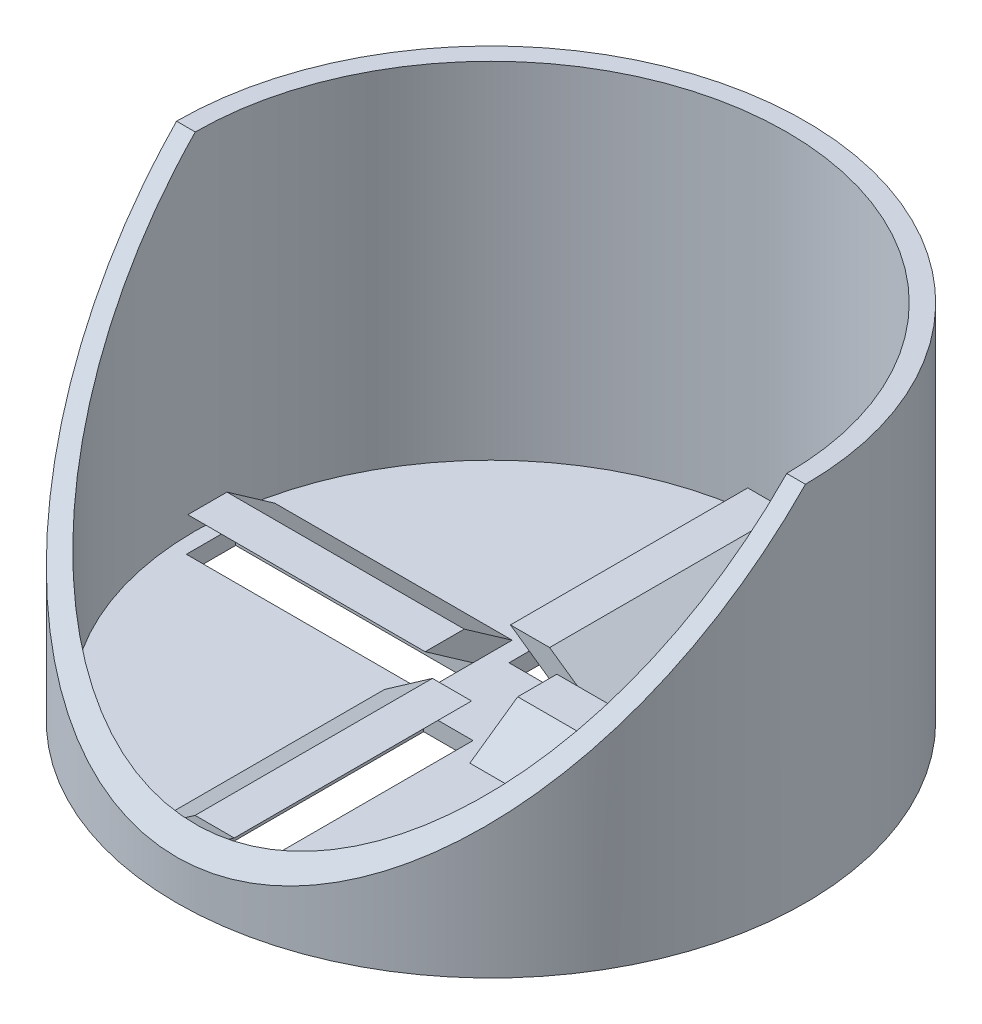
SolidWorks part; units mm, degrees
ref_plane "Front Plane" through (0, 0, 0) normal (0, 0, 1) x (1, 0, 0)
ref_plane "Top Plane" through (0, 0, 0) normal (0, 1, 0) x (1, 0, 0)
ref_plane "Right Plane" through (0, 0, 0) normal (1, 0, 0) x (0, 0, -1)
sketch "Sketch1" plane through (0, 0, 0) normal (0, 1, 0) x (1, 0, 0)
  circle A0 centre (0, 0) radius 44.137
extrude "Boss-Extrude1" add sketch "Sketch1" along normal blind 2.54
sketch "Sketch2" plane through (0, 2.54, 0) normal (0, 1, 0) x (1, 0, 0)
  line L0 (0, 0) -> (0, 44.137) construction
  line L1 (-3.682, 6.3677) -> (3.682, 6.3677)
  line L2 (-3.682, 6.3677) -> (-3.682, 41.7813)
  line L3 (-3.682, 41.7813) -> (3.682, 41.7813)
  line L4 (3.682, 6.3677) -> (3.682, 41.7813)
  line L5 (-3.682, 6.3677) -> (3.682, 41.7813) construction
  line L6 (-3.682, 41.7813) -> (3.682, 6.3677) construction
  circle A0 centre (0, 0) radius 44.137 construction
  point P0 (0, 24.0745)
  point P11 (0, 0)
extrude "Cut-Extrude1" cut sketch "Sketch2" against normal blind 2.54
sketch "Sketch3" plane through (0, 0, 0) normal (0, 0, 1) x (1, 0, 0)
  line L0 (3.682, 2.54) -> (-3.4646, 7.5441)
  line L1 (-3.4646, 7.5441) -> (2.3783, 7.5441)
  line L2 (2.3783, 7.5441) -> (9.5249, 2.54)
  line L3 (44.137, 2.54) -> (-44.137, 2.54) construction
  line L4 (3.682, 2.54) -> (9.5249, 2.54)
  dimension "D1" = 35
extrude "Boss-Extrude2" add sketch "Sketch3" against normal up to surface (35.4136 mm away) from surface at -6.3677 up to face at (0, 1.27, -41.7813) starting at face at (0, 1.27, -6.3677)
pattern_circular "CirPattern3" count 4 over 360 about axis through (0, 0, 0) along (0, 1, 0) of "Cut-Extrude1", "Boss-Extrude2"
sketch "Sketch4" plane through (0, 2.54, 0) normal (0, 1, 0) x (1, 0, 0)
  line L0 (0, 0) -> (0, 6.3677) construction
  line L1 (-3.682, 6.3677) -> (3.682, 6.3677) construction
  line L2 (0, 6.3677) -> (0, 41.7813) construction
  line L3 (3.682, 41.7813) -> (-3.682, 41.7813) construction
  circle A0 centre (0, 0) radius 24.0745 construction
  point P9 (0, 24.0745)
  point P10 (0, 0)
sketch "Sketch6" plane through (0, 0, 0) normal (0, 1, 0) x (1, 0, 0)
  circle A0 centre (0, 0) radius 46.9292
  circle A1 centre (0, 0) radius 44.137 construction
  circle A2 centre (0, 0) radius 44.137
extrude "Boss-Extrude3" add sketch "Sketch6" along normal blind 54.102
sketch "Sketch7" plane through (0, 0, 0) normal (1, 0, 0) x (0, 0, -1)
  line L0 (0, 54.102) -> (-46.9292, 5.9137)
  line L1 (44.137, 54.102) -> (-44.137, 54.102) construction
  line L2 (-46.9292, 54.102) -> (-46.9292, 0) construction
  line L3 (-46.9292, 5.9137) -> (-46.9292, 54.102)
  line L4 (-46.9292, 54.102) -> (0, 54.102)
extrude "Cut-Extrude2" cut sketch "Sketch7" against normal through all both and the other way through all
